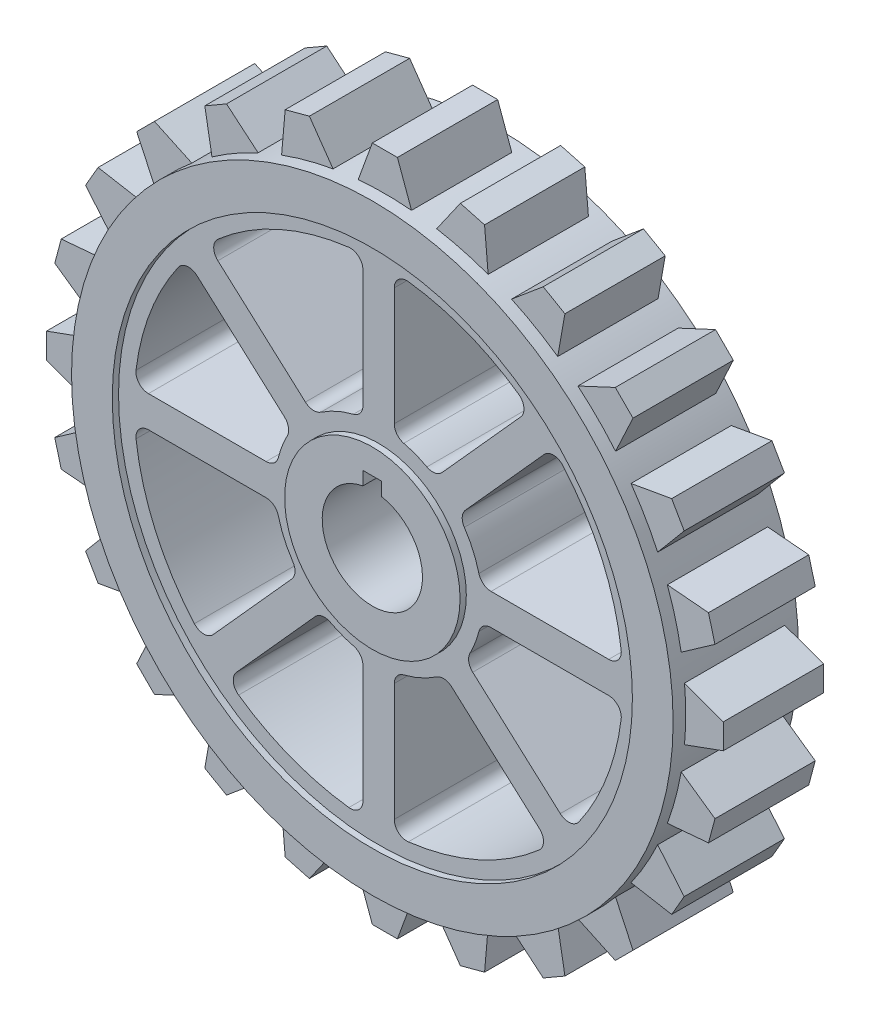
SolidWorks part; units mm, degrees
ref_plane "Płaszczyzna przednia" through (0, 0, 0) normal (0, 0, 1) x (1, 0, 0)
ref_plane "Płaszczyzna górna" through (0, 0, 0) normal (0, 1, 0) x (1, 0, 0)
ref_plane "Płaszczyzna prawa" through (0, 0, 0) normal (1, 0, 0) x (0, 0, -1)
ref_plane "Płaszczyzna1" through (0, 0, -1) normal (0, 0, 1) x (1, 0, 0)
sketch "Szkic3" plane through (0, 0, -1) normal (0, 0, 1) x (1, 0, 0)
  line L0 (0, 0) -> (0, 10) construction
  line L1 (-1.5, 10) -> (1.5, 10)
  line L2 (-1.5, 10) -> (-1.5, 7.8581)
  line L3 (-1.5, 7.8581) -> (1.5, 7.8581)
  line L4 (1.5, 7.8581) -> (1.5, 10)
  circle A0 centre (0, 0) radius 8
  circle A1 centre (0, 0) radius 14
  circle A2 centre (0, 0) radius 48
  circle A3 centre (0, 0) radius 41.5
  dimension "D1" = 16
  dimension "D2" = 28
  dimension "D5" = 96
  dimension "D3" = 3
  dimension "D4" = 10
  dimension "D6" = 6.5
extrude "Dodanie-wyciągnięcie1" add sketch "Szkic3" along normal blind 20 contours A2 A3 | A1 A0 L2 L1 L4
sketch "Szkic4" plane through (0, 0, 0) normal (0, 0, 1) x (1, 0, 0)
  line L0 (0, 0) -> (0, 39) construction
  line L1 (0, 0) -> (39, 0) construction
  line L2 (2.5, 36.7253) -> (2.5, 17.9444)
  line L3 (22.6825, 28.9914) -> (10.1318, 15.0199)
  line L4 (26.4021, 25.6501) -> (13.8514, 11.6785)
  line L5 (17.9444, 2.5) -> (36.7253, 2.5)
  line L6 (0, 0) -> (26.0624, 29.0129) construction
  line L7 (36.7253, -2.5) -> (17.9444, -2.5)
  line L8 (28.9914, -22.6825) -> (15.0199, -10.1318)
  line L9 (25.6501, -26.4021) -> (11.6785, -13.8514)
  line L10 (2.5, -17.9444) -> (2.5, -36.7253)
  line L11 (-2.5, -36.7253) -> (-2.5, -17.9444)
  line L12 (-22.6825, -28.9914) -> (-10.1318, -15.0199)
  line L13 (-26.4021, -25.6501) -> (-13.8514, -11.6785)
  line L14 (-17.9444, -2.5) -> (-36.7253, -2.5)
  line L15 (-36.7253, 2.5) -> (-17.9444, 2.5)
  line L16 (-28.9914, 22.6825) -> (-15.0199, 10.1318)
  line L17 (-25.6501, 26.4021) -> (-11.6785, 13.8514)
  line L18 (-2.5, 17.9444) -> (-2.5, 36.7253)
  circle A0 centre (0, 0) radius 41.5 construction
  circle A1 centre (0, 0) radius 41.5
  circle A2 centre (0, 0) radius 39
  circle A3 centre (0, 0) radius 14 construction
  circle A4 centre (0, 0) radius 14
  circle A5 centre (0, 0) radius 16.5
  arc A6 (2.5, 17.9444) -> (4.0135, 16.0044) centre (4.5, 17.9444) ccw
  arc A7 (22.6825, 28.9914) -> (22.3404, 31.9673) centre (21.1947, 30.328) ccw
  arc A8 (2.5, 36.7253) -> (4.7432, 38.7105) centre (4.5, 36.7253) cw
  arc A9 (7.7095, 14.5881) -> (10.1318, 15.0199) centre (8.644, 16.3564) ccw
  arc A10 (13.8514, 11.6785) -> (13.681, 9.2239) centre (15.3393, 10.342) ccw
  arc A11 (16.0044, 4.0135) -> (17.9444, 2.5) centre (17.9444, 4.5) ccw
  arc A12 (36.7253, 2.5) -> (38.7105, 4.7432) centre (36.7253, 4.5) ccw
  arc A13 (26.4021, 25.6501) -> (29.3975, 25.6278) centre (27.89, 24.3136) cw
  arc A14 (17.9444, -2.5) -> (16.0044, -4.0135) centre (17.9444, -4.5) ccw
  circle A15 centre (0, 0) radius 16.5
  arc A16 (14.5881, -7.7095) -> (15.0199, -10.1318) centre (16.3564, -8.644) ccw
  arc A17 (28.9914, -22.6825) -> (31.9673, -22.3404) centre (30.328, -21.1947) ccw
  arc A18 (36.7253, -2.5) -> (38.7105, -4.7432) centre (36.7253, -4.5) cw
  arc A19 (11.6785, -13.8514) -> (9.2239, -13.681) centre (10.342, -15.3393) ccw
  arc A20 (25.6501, -26.4021) -> (25.6278, -29.3975) centre (24.3136, -27.89) cw
  circle A21 centre (0, 0) radius 39
  arc A22 (2.5, -36.7253) -> (4.7432, -38.7105) centre (4.5, -36.7253) ccw
  arc A23 (4.0135, -16.0044) -> (2.5, -17.9444) centre (4.5, -17.9444) ccw
  arc A24 (-2.5, -17.9444) -> (-4.0135, -16.0044) centre (-4.5, -17.9444) ccw
  circle A25 centre (0, 0) radius 16.5
  arc A26 (-7.7095, -14.5881) -> (-10.1318, -15.0199) centre (-8.644, -16.3564) ccw
  arc A27 (-22.6825, -28.9914) -> (-22.3404, -31.9673) centre (-21.1947, -30.328) ccw
  arc A28 (-2.5, -36.7253) -> (-4.7432, -38.7105) centre (-4.5, -36.7253) cw
  arc A29 (-13.8514, -11.6785) -> (-13.681, -9.2239) centre (-15.3393, -10.342) ccw
  arc A30 (-26.4021, -25.6501) -> (-29.3975, -25.6278) centre (-27.89, -24.3136) cw
  circle A31 centre (0, 0) radius 39
  arc A32 (-36.7253, -2.5) -> (-38.7105, -4.7432) centre (-36.7253, -4.5) ccw
  arc A33 (-16.0044, -4.0135) -> (-17.9444, -2.5) centre (-17.9444, -4.5) ccw
  arc A34 (-17.9444, 2.5) -> (-16.0044, 4.0135) centre (-17.9444, 4.5) ccw
  circle A35 centre (0, 0) radius 16.5
  arc A36 (-14.5881, 7.7095) -> (-15.0199, 10.1318) centre (-16.3564, 8.644) ccw
  arc A37 (-28.9914, 22.6825) -> (-31.9673, 22.3404) centre (-30.328, 21.1947) ccw
  arc A38 (-36.7253, 2.5) -> (-38.7105, 4.7432) centre (-36.7253, 4.5) cw
  arc A39 (-11.6785, 13.8514) -> (-9.2239, 13.681) centre (-10.342, 15.3393) ccw
  arc A40 (-25.6501, 26.4021) -> (-25.6278, 29.3975) centre (-24.3136, 27.89) cw
  circle A41 centre (0, 0) radius 39
  arc A42 (-2.5, 36.7253) -> (-4.7432, 38.7105) centre (-4.5, 36.7253) ccw
  arc A43 (-4.0135, 16.0044) -> (-2.5, 17.9444) centre (-4.5, 17.9444) ccw
  point P118 (0, 0)
  dimension "D6" = 2
  dimension "D7" = 2.5
  dimension "D8" = 2
  dimension "D9" = 2
  dimension "D10" = 2
  dimension "D11" = 2
  dimension "D12" = 2
  dimension "D13" = 2
  dimension "D15" = 2
  dimension "D3" = 2.5
  dimension "D4" = 2.5
  dimension "D5" = 2.5
  dimension "D14" = 48.067
  dimension "D1" = 2.5
  dimension "D2" = 2.5
  dimension "D16" = 4
extrude "Dodanie-wyciągnięcie2" add sketch "Szkic4" along normal blind 18 contours A1 A2 A21 A31 A41 | L15 A38 A2 A32 L14 A33 A25 A34 | L17 A40 A31 A37 L16 A36 A35 A39 | A5 A35 A25 A15 A4 | A43 A5 A6 L2 A8 A2 A42 L18 | L4 A13 A2 A7 L3 A9 A5 A10 | L7 A18 A2 A12 L5 A11 A5 A14 | L9 A20 A2 A17 L8 A16 A15 A19 | L11 A28 A2 A22 L10 A23 A15 A24 | L13 A30 A21 A27 L12 A26 A25 A29
ref_plane "Płaszczyzna2" through (0, 0, 1) normal (0, 0, 1) x (1, 0, 0)
sketch "Szkic6" plane through (0, 0, 1) normal (0, 0, 1) x (1, 0, 0)
  line L0 (0, 0) -> (0, 54) construction
  line L1 (-2, 54) -> (2, 54)
  line L2 (-2, 54) -> (-4.2525, 47.8113)
  line L3 (2, 54) -> (4.2525, 47.8113)
  circle A0 centre (0, 0) radius 48 construction
  circle A2 centre (0, 0) radius 48
  circle A3 centre (0, 0) radius 48
  dimension "D1" = 54
  dimension "D2" = 4
  dimension "D3" = 40
  dimension "D4" = 0
extrude "Dodanie-wyciągnięcie3" add sketch "Szkic6" along normal blind 16 contours L0 A3 L3 L1 | A3 L0 L1 L2
pattern_circular "Szyk kołowy1" count 24 every 15 about axis through (0, 0, 0) along (0, 0, 1) of "Dodanie-wyciągnięcie3"
